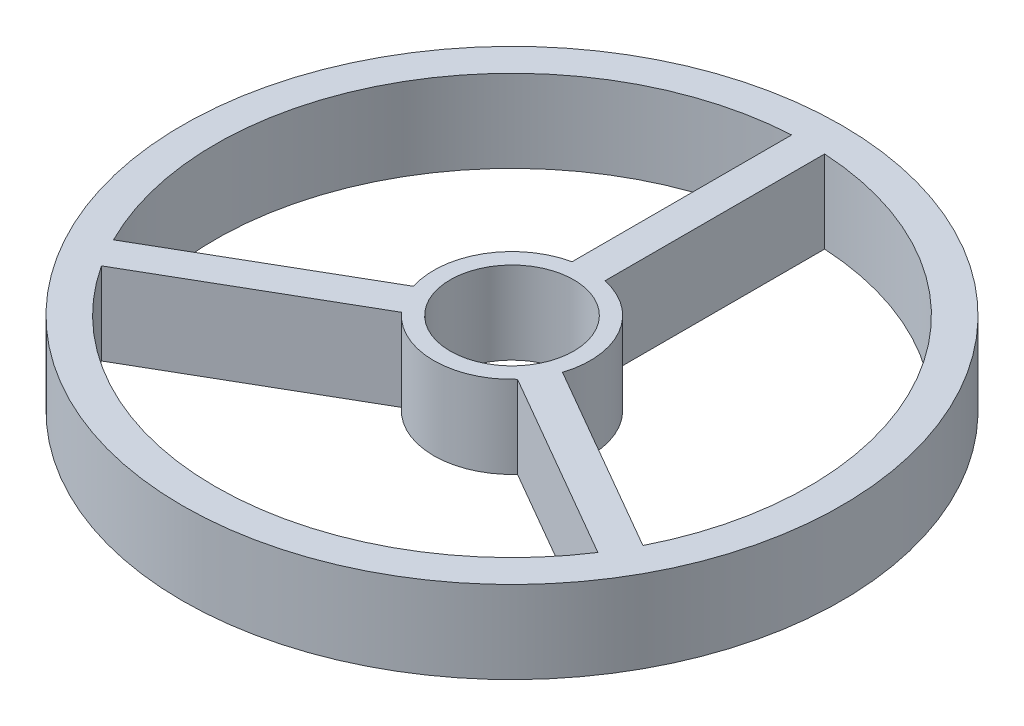
SolidWorks part; units mm, degrees
ref_plane "Front Plane" through (0, 0, 0) normal (0, 0, 1) x (1, 0, 0)
ref_plane "Top Plane" through (0, 0, 0) normal (0, 1, 0) x (1, 0, 0)
ref_plane "Right Plane" through (0, 0, 0) normal (1, 0, 0) x (0, 0, -1)
sketch "Sketch2" plane through (0, 0, 0) normal (0, 1, 0) x (1, 0, 0)
  line L3 (-2, 35.9444) -> (-2, 9.2871)
  line L4 (2, 35.9444) -> (2, 9.2871)
  line L6 (-9.0429, -2.9115) -> (-32.1288, -16.2401)
  line L7 (9.0429, -2.9115) -> (32.1288, -16.2401)
  line L8 (0, -7.5) -> (0, -40) construction
  line L9 (-7.0429, -6.3756) -> (-30.1288, -19.7043)
  line L11 (7.0429, -6.3756) -> (30.1288, -19.7043)
  circle A3 centre (0, 0) radius 40
  arc A4 (-30.1288, -19.7043) -> (30.1288, -19.7043) centre (0, 0) ccw
  arc A5 (32.1288, -16.2401) -> (2, 35.9444) centre (0, 0) ccw
  arc A7 (-2, 35.9444) -> (-32.1288, -16.2401) centre (0, 0) ccw
  circle A8 centre (0, 0) radius 7.5
  arc A9 (-7.0429, -6.3756) -> (7.0429, -6.3756) centre (0, 0) ccw
  circle A10 centre (0, 0) radius 9.5 construction
  arc A11 (9.0429, -2.9115) -> (2, 9.2871) centre (0, 0) ccw
  arc A12 (-2, 9.2871) -> (-9.0429, -2.9115) centre (0, 0) ccw
  dimension "D1" = 4
  dimension "D2" = 120
  dimension "D5" = 9.5
  dimension "D3" = 36
  dimension "D7" = 80
  dimension "D8" = 2
  dimension "D4" = 60.2575
  dimension "D6" = 26.6573
extrude "Boss-Extrude1" add sketch "Sketch2" along normal mid plane 10
